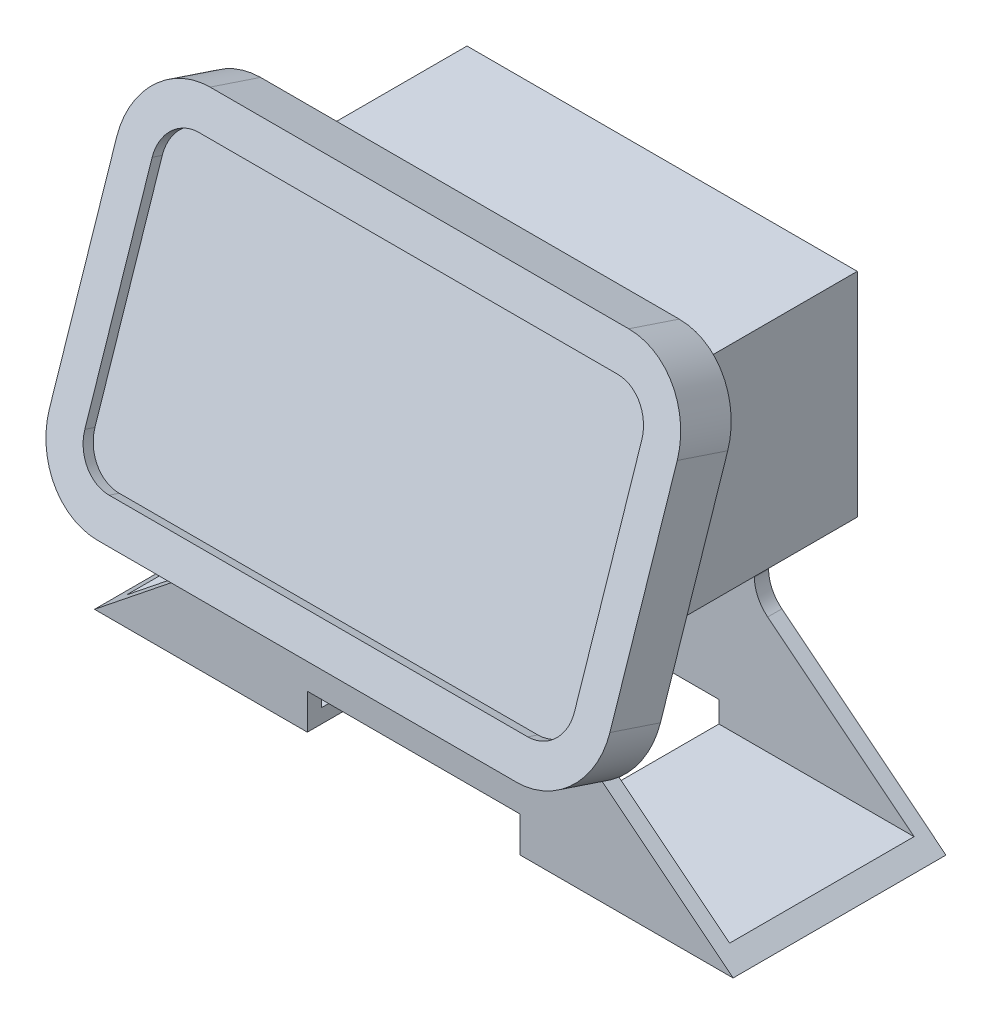
SolidWorks part; units mm, degrees
ref_plane "前视基准面" through (0, 0, 0) normal (0, 0, 1) x (1, 0, 0)
ref_plane "上视基准面" through (0, 0, 0) normal (0, 1, 0) x (1, 0, 0)
ref_plane "右视基准面" through (0, 0, 0) normal (1, 0, 0) x (0, 0, -1)
other "Configuration Table"
sketch "草图1" plane through (0, 0, 0) normal (0, 0, 1) x (1, 0, 0)
  line L0 (-90, 0) -> (-40, 40)
  line L1 (-90, 0) -> (90, 0)
  line L5 (90, 0) -> (40, 40)
  line L9 (-30, 0) -> (30, 0)
  line L10 (-30, 0) -> (-30, 10)
  line L11 (-30, 10) -> (30, 10)
  line L12 (30, 0) -> (30, 10)
  line L13 (-40, 40) -> (40, 40)
  point P4 (0, 0)
  point P13 (0, 10)
  point P14 (0, 40)
  dimension "D1" = 40
  dimension "D3" = 80
  dimension "D4" = 60
  dimension "D5" = 10
  dimension "160" = 180
extrude "凸台-拉伸1" add sketch "草图1" along normal mid plane 60
sketch "草图2" plane through (0, 40, 0) normal (0, 1, 0) x (1, 0, 0)
  line L4 (40, 30) -> (-40, 30)
  line L5 (-40, 30) -> (-40, -30)
  line L6 (-40, -30) -> (40, -30)
  line L7 (40, -30) -> (40, 30)
  line L8 (40, 30) -> (-40, 30)
  line L9 (-40, 30) -> (-40, -30)
  line L10 (-40, -30) -> (40, -30)
  line L11 (40, -30) -> (40, 30)
  dimension "D1" = 0
extrude "凸台-拉伸2" add sketch "草图2" along normal blind 20
fillet "圆角1" radius 10 2 edges at (40, 40, 0) (-40, 40, 0)
sketch "草图3" plane through (0, 0, 30) normal (0, 0, 1) x (1, 0, 0)
  line L0 (-40, 60) -> (40, 60) construction
  line L1 (-30, 60) -> (30, 60)
  line L2 (-30, 60) -> (-30, 40)
  line L3 (-30, 40) -> (30, 40)
  line L4 (30, 60) -> (30, 40)
  line L5 (-30, 0) -> (-30, 10) construction
  line L6 (30, 0) -> (30, 10) construction
  dimension "D1" = 20
extrude "切除-拉伸1" cut sketch "草图3" against normal through all
sketch "草图4" plane through (0, 60, 0) normal (0, 1, 0) x (1, 0, 0)
  line L1 (-55, -40) -> (55, -40)
  line L2 (-55, -40) -> (-55, 40)
  line L3 (-55, 40) -> (55, 40)
  line L4 (55, -40) -> (55, 40)
  line L5 (-55, -40) -> (55, 40) construction
  line L6 (-55, 40) -> (55, -40) construction
  point P0 (0, 0)
  dimension "D1" = 110
  dimension "D2" = 80
extrude "凸台-拉伸3" add sketch "草图4" along normal blind 60
sketch "草图5" plane through (-55, 0, 0) normal (-1, 0, 0) x (0, 0, 1)
  line L0 (40, 60) -> (20, 120)
  line L4 (-40, 60) -> (40, 60)
  line L5 (40, 60) -> (40, 120)
  line L6 (40, 120) -> (-40, 120)
  line L7 (-40, 120) -> (-40, 60)
  line L8 (-40, 60) -> (40, 60)
  line L9 (40, 60) -> (40, 120)
  line L10 (40, 120) -> (-40, 120)
  line L11 (-40, 120) -> (-40, 60)
  line M6 (40, 60) -> (40, 120)
  line M7 (40, 120) -> (-40, 120)
  dimension "D2" = 20
  dimension "D1" = 0
extrude "切除-拉伸2" cut sketch "草图5" against normal through all contours L0 M6 M7
sketch "草图6" plane through (0, 18, 54) normal (0, 0.3162, 0.9487) x (1, 0, 0)
  line L0 (55, 44.2719) -> (55, 107.5174) construction
  line L1 (-79, 25.8947) -> (79, 25.8947)
  line L2 (-79, 25.8947) -> (-79, 125.8947)
  line L3 (-79, 125.8947) -> (79, 125.8947)
  line L12 (79, 25.8947) -> (79, 125.8947)
  line L13 (-79, 25.8947) -> (79, 125.8947) construction
  line L14 (-79, 125.8947) -> (79, 25.8947) construction
  line L15 (55, 44.2719) -> (55, 107.5174)
  point P0 (0, 75.8947)
  point P9 (55, 75.8947)
  line M6 (55, 44.2719) -> (55, 107.5174)
  line M7 (55, 107.5174) -> (-55, 107.5174)
  line M8 (-55, 107.5174) -> (-55, 44.2719)
  line M9 (-55, 44.2719) -> (55, 44.2719)
  dimension "D1" = 158
  dimension "D2" = 100
extrude "凸台-拉伸4" add sketch "草图6" along normal blind 15 contours L1 L12 L3 L2 M6 M9 M8 M7 | M9 M6 M7 M8
fillet "圆角2" radius 20 4 edges at (79, 139.8059, 21.3037) (79, 44.9375, 52.9265) (-79, 44.9375, 52.9265) (-79, 139.8059, 21.3037)
sketch "草图7" plane through (0, 22.7434, 68.2302) normal (0, 0.3162, 0.9487) x (1, 0, 0)
  line L0 (-69, 105.8947) -> (-69, 45.8947)
  line L1 (-59, 35.8947) -> (59, 35.8947)
  line L2 (69, 45.8947) -> (69, 105.8947)
  line L3 (59, 115.8947) -> (-59, 115.8947)
  line L4 (79, 45.8947) -> (79, 105.8947)
  line L5 (59, 125.8947) -> (-59, 125.8947)
  line L6 (-79, 105.8947) -> (-79, 45.8947)
  line L7 (-59, 25.8947) -> (59, 25.8947)
  line L8 (79, 45.8947) -> (79, 105.8947)
  line L9 (59, 125.8947) -> (-59, 125.8947)
  line L10 (-79, 105.8947) -> (-79, 45.8947)
  line L11 (-59, 25.8947) -> (59, 25.8947)
  arc A0 (-59, 115.8947) -> (-69, 105.8947) centre (-59, 105.8947) ccw
  arc A1 (-69, 45.8947) -> (-59, 35.8947) centre (-59, 45.8947) ccw
  arc A2 (59, 35.8947) -> (69, 45.8947) centre (59, 45.8947) ccw
  arc A3 (69, 105.8947) -> (59, 115.8947) centre (59, 105.8947) ccw
  arc A4 (79, 105.8947) -> (59, 125.8947) centre (59, 105.8947) ccw
  arc A5 (-59, 125.8947) -> (-79, 105.8947) centre (-59, 105.8947) ccw
  arc A6 (-79, 45.8947) -> (-59, 25.8947) centre (-59, 45.8947) ccw
  arc A7 (59, 25.8947) -> (79, 45.8947) centre (59, 45.8947) ccw
  arc A8 (79, 105.8947) -> (59, 125.8947) centre (59, 105.8947) ccw
  arc A9 (-59, 125.8947) -> (-79, 105.8947) centre (-59, 105.8947) ccw
  arc A10 (-79, 45.8947) -> (-59, 25.8947) centre (-59, 45.8947) ccw
  arc A11 (59, 25.8947) -> (79, 45.8947) centre (59, 45.8947) ccw
  dimension "D1" = 0
  dimension "D2" = 10
extrude "切除-拉伸3" cut sketch "草图7" against normal blind 3 contours L2 A3 L3 A0 L0 A1 L1 A2
sketch "草图8" plane through (55, 0, 0) normal (1, 0, 0) x (0, 0, -1)
  line L0 (30, 0) -> (30, 36.9976) construction
  line L1 (-26, 4) -> (26, 4)
  line L2 (-26, 4) -> (-26, 60)
  line L3 (-26, 60) -> (26, 60)
  line L4 (26, 4) -> (26, 60)
  line L5 (-30, 0) -> (30, 0) construction
  line L6 (-30, 0) -> (-30, 36.9976) construction
  line L7 (-40, 60) -> (40, 60) construction
  dimension "D1" = 4
  dimension "D2" = 4
  dimension "D3" = 4
extrude "切除-拉伸4" cut sketch "草图8" against normal through all both and the other way through all
